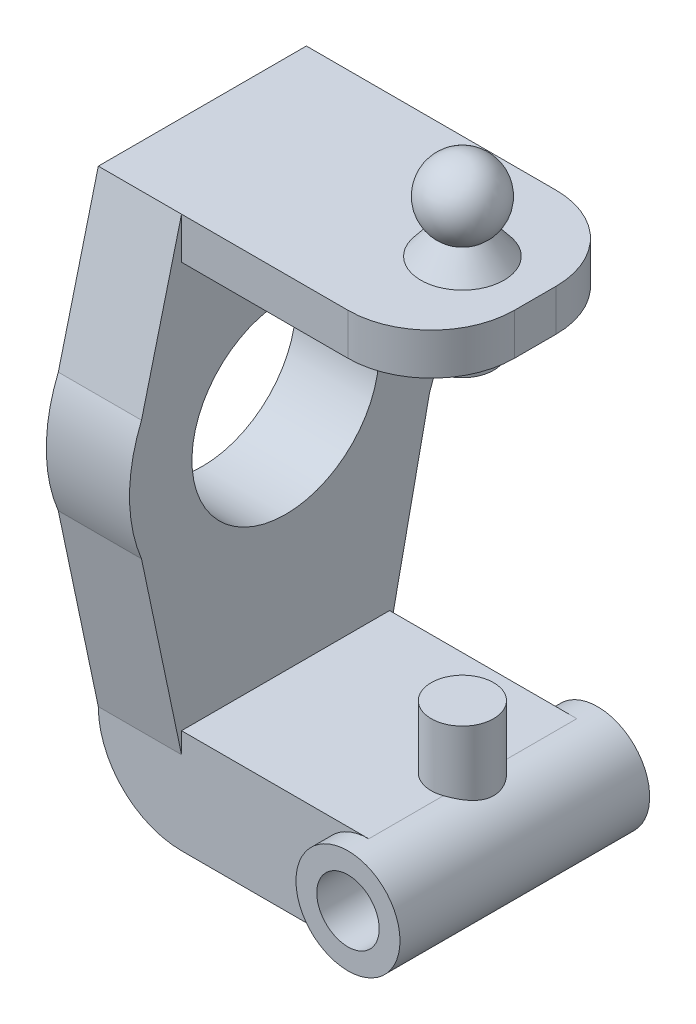
SolidWorks part; units mm, degrees
ref_plane "前视基准面" through (0, 0, 0) normal (0, 0, 1) x (1, 0, 0)
ref_plane "上视基准面" through (0, 0, 0) normal (0, 1, 0) x (1, 0, 0)
ref_plane "右视基准面" through (0, 0, 0) normal (1, 0, 0) x (0, 0, -1)
sketch "草图1" plane through (0, 0, 0) normal (0, 0, 1) x (1, 0, 0)
  line L0 (4, 0) -> (13, 0)
  line L2 (13, 5) -> (4, 5)
  line L3 (4, 5) -> (4, 24.5)
  line L4 (4, 24.5) -> (16, 24.5)
  line L5 (16, 24.5) -> (16, 26.5)
  line L6 (16, 26.5) -> (0, 26.5)
  line L7 (0, 26.5) -> (0, 4)
  circle A0 centre (13, 2.5) radius 1.5
  arc A1 (13, 0) -> (13, 5) centre (13, 2.5) ccw
  arc A2 (0, 4) -> (4, 0) centre (4, 4) ccw
  point P9 (0, 0)
  dimension "D2" = 4
  dimension "D16" = 2.5
  dimension "D3" = 3
  dimension "D6" = 90
  dimension "D7" = 90
  dimension "D8" = 90
  dimension "D9" = 90
  dimension "D10" = 19.5
  dimension "D11" = 12
  dimension "D12" = 2
  dimension "D13" = 26.5
  dimension "D14" = 16
extrude "凸台-拉伸1" add sketch "草图1" along normal blind 10
sketch "草图2" plane through (0, 0, 0) normal (0, 0, -1) x (-1, 0, 0)
  circle A0 centre (-13, 2.5) radius 2.5
  circle A1 centre (-13, 2.5) radius 1.5
extrude "凸台-拉伸2" add sketch "草图2" along normal blind 1
sketch "草图3" plane through (0, 0, 10) normal (0, 0, 1) x (1, 0, 0)
  circle A0 centre (13, 2.5) radius 1.5
  circle A1 centre (13, 2.5) radius 2.5
extrude "凸台-拉伸3" add sketch "草图3" along normal blind 1
sketch "草图4" plane through (0, 26.5, 0) normal (0, 1, 0) x (1, 0, 0)
  line L0 (0, -5) -> (12.5, -5)
  line L1 (0, -10) -> (0, 0) construction
ref_plane "基准面1" through (12.5, 0, 0) normal (-1, 0, 0) x (0, 0, 1)
fillet "圆角1" radius 4 2 edges at (16, 25.5, 0) (16, 25.5, 10)
sketch "草图6" plane through (0, 24.5, 0) normal (0, -1, 0) x (1, 0, 0)
  line L0 (4, 10) -> (12, 10) construction
  line L1 (4, 10) -> (4, 0) construction
  circle A0 centre (12.5, 5) radius 1.5
  dimension "D1" = 3
  dimension "D2" = 5
  dimension "D3" = 8.5
extrude "凸台-拉伸4" add sketch "草图6" along normal blind 2
sketch "草图7" plane through (0, 5, 0) normal (0, 1, 0) x (1, 0, 0)
  line L0 (4, -10) -> (4, 0) construction
  line L1 (13, 0) -> (4, 0) construction
  circle A0 centre (12.5, -5) radius 1.5
  dimension "D1" = 3
  dimension "D3" = 5
  dimension "D2" = 8.5
extrude "凸台-拉伸5" add sketch "草图7" along normal mid plane 2
sketch "草图8" plane through (0, 6, 0) normal (0, 1, 0) x (1, 0, 0)
  circle A0 centre (12.5, -5) radius 1.5
extrude "凸台-拉伸6" add sketch "草图8" along normal blind 2
sketch "草图9" plane through (0, 0, 0) normal (-1, 0, 0) x (0, 0, 1)
  line L0 (10, 4) -> (0, 4) construction
  line L1 (10, 26.5) -> (10, 4) construction
  line L2 (10, 26.5) -> (11.9231, 18.8846)
  line L3 (11.9231, 13.1154) -> (10, 4)
  line L4 (0, 26.5) -> (-1.9231, 18.8846)
  line L5 (-1.9231, 13.1154) -> (0, 4)
  line L6 (10, 26.5) -> (0, 26.5)
  line L7 (0, 4) -> (10, 4)
  arc A0 (-1.9231, 18.8846) -> (-1.9231, 13.1154) centre (5, 16) ccw
  arc A1 (11.9231, 13.1154) -> (11.9231, 18.8846) centre (5, 16) ccw
  dimension "D1" = 15
  dimension "D3" = 5
  dimension "D2" = 12
extrude "凸台-拉伸7" add sketch "草图9" against normal blind 4
sketch "草图10" plane through (0, 0, 0) normal (-1, 0, 0) x (0, 0, 1)
  line L0 (10, 4) -> (0, 4) construction
  circle A0 centre (5, 16) radius 4.5
  dimension "D1" = 12
  dimension "D2" = 5
extrude "切除-拉伸1" cut sketch "草图10" against normal blind 4
sketch "草图11" plane through (12.5, 0, 0) normal (-1, 0, 0) x (0, 0, 1)
  line L0 (5, 26.5) -> (3, 26.5)
  line L1 (5, 26.5) -> (5, 29)
  line L2 (3, 26.5) -> (3.9135, 27.6418)
  line L3 (5, 29) -> (5, 30.7393)
  arc A0 (5, 30.7393) -> (3.9135, 27.6418) centre (5, 29) ccw
  dimension "D1" = 2.5
revolve "旋转1" add sketch "草图11" angle 360 about L3
